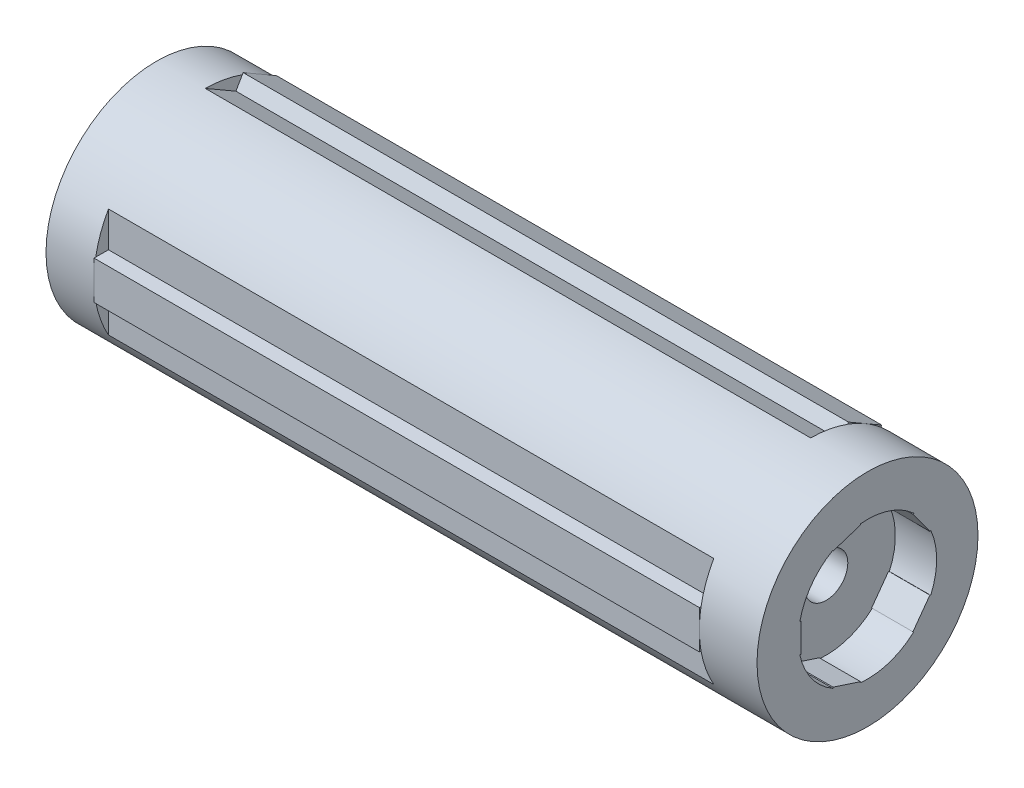
SolidWorks part; units mm, degrees
material "PVC hart"
ref_plane "Ebene vorne" through (0, 0, 0) normal (0, 0, 1) x (1, 0, 0)
ref_plane "Ebene oben" through (0, 0, 0) normal (0, 1, 0) x (1, 0, 0)
ref_plane "Ebene rechts" through (0, 0, 0) normal (1, 0, 0) x (0, 0, -1)
sketch "Skizze1" plane through (0, 0, 0) normal (1, 0, 0) x (0, 0, -1)
  circle A0 centre (0, 0) radius 11.5
  dimension "D1" = 23
extrude "Grundkörper Walze" add sketch "Skizze1" along normal blind 74
sketch "Skizze2" plane through (74, 0, 0) normal (1, 0, 0) x (0, 0, -1)
  line L0 (-15.3822, 0) -> (15.9559, 0) construction
  line L1 (-7.0405, 1.5073) -> (-6.9405, 1.5073)
  line L2 (-6.9405, 1.5073) -> (-6.9405, -1.4927)
  line L3 (-6.9405, -1.4927) -> (-7.0436, -1.4927)
  line L4 (-0.7421, 7.1617) -> (-0.7112, 7.0666)
  line L5 (-0.7112, 7.0666) -> (-3.5643, 6.1395)
  line L6 (-3.5643, 6.1395) -> (-3.5962, 6.2376)
  line L7 (6.5818, 2.9188) -> (6.5009, 2.86)
  line L8 (6.5009, 2.86) -> (4.7376, 5.2871)
  line L9 (4.7376, 5.2871) -> (4.821, 5.3477)
  line L10 (4.8099, -5.3577) -> (4.729, -5.2989)
  line L11 (4.729, -5.2989) -> (6.4923, -2.8719)
  line L12 (6.4923, -2.8719) -> (6.5757, -2.9325)
  line L13 (-3.6092, -6.2301) -> (-3.5783, -6.135)
  line L14 (-3.5783, -6.135) -> (-0.7251, -7.062)
  line L15 (-0.7251, -7.062) -> (-0.757, -7.1601)
  arc A0 (-7.0436, -1.4927) -> (-3.6092, -6.2301) centre (0, 0) ccw
  arc A1 (-3.5962, 6.2376) -> (-7.0405, 1.5073) centre (0, 0) ccw
  arc A2 (4.821, 5.3477) -> (-0.7421, 7.1617) centre (0, 0) ccw
  arc A3 (6.5757, -2.9325) -> (6.5818, 2.9188) centre (0, 0) ccw
  arc A4 (-0.757, -7.1601) -> (4.8099, -5.3577) centre (0, 0) ccw
  point P28 (0, 0)
  dimension "D1" = 14.4
  dimension "D2" = 3
  dimension "D3" = 0.1
  dimension "D4" = 5
extrude "Presspassung Kugellager" cut sketch "Skizze2" against normal blind 4.3
sketch "Skizze3" plane through (69.7, 0, 0) normal (1, 0, 0) x (0, 0, -1)
  circle A0 centre (0, 0) radius 2.25
  dimension "D1" = 4.5
extrude "M4 Schraubenführung" cut sketch "Skizze3" against normal blind 4.5
sketch "Skizze4" plane through (0, 0, 0) normal (-1, 0, 0) x (0, 0, 1)
  circle A0 centre (0, 0) radius 9.6
  dimension "D1" = 19.2
extrude "Motoraussparung " cut sketch "Skizze4" against normal blind 12.75
sketch "Skizze7" plane through (74, 0, 0) normal (1, 0, 0) x (0, 0, -1)
  line L0 (0, 13.4409) -> (0, -14.2481) construction
  line L1 (-11.5, 7.5) -> (-10, 7.5)
  line L2 (-11.5, 7.5) -> (-11.5, -7.5)
  line L3 (-11.5, -7.5) -> (-10, -7.5)
  line L4 (-10, 7.5) -> (-10, -7.5)
  dimension "D1" = 1.5
  dimension "D2" = 15
  dimension "D3" = 10
extrude "Zerstörungselement Aussparung" cut sketch "Skizze7" against normal blind 63 from offset 6 offset against normal yes
sketch "Skizze8" plane through (0, 0, 10) normal (0, 0, 1) x (1, 0, 0)
  line L0 (68, -5.6789) -> (68, 5.6789) construction
  line L1 (5, 2) -> (68, 2)
  line L2 (5, 2) -> (5, -2)
  line L3 (5, -2) -> (68, -2)
  line L4 (68, 2) -> (68, -2)
  line L5 (5, 2) -> (68, -2) construction
  line L6 (5, -2) -> (68, 2) construction
  line L7 (55, 0) -> (-55, 0) construction
  point P0 (36.5, 0)
  dimension "D1" = 31.5
  dimension "D3" = 63
  dimension "D4" = 4
extrude "Zerstörungselement Rechteck" add sketch "Skizze8" along normal blind 1.5
sketch "Skizze10" plane through (12.75, 0, 0) normal (-1, 0, 0) x (0, 0, 1)
  line L1 (4.1398, -2.2968) -> (4.059, 2.4368)
  line L2 (4.059, 2.4368) -> (-0.0809, 4.7336)
  line L3 (-0.0809, 4.7336) -> (-4.1398, 2.2968)
  line L4 (-4.1398, 2.2968) -> (-4.059, -2.4368)
  line L5 (-4.059, -2.4368) -> (0.0809, -4.7336)
  line L6 (0.0809, -4.7336) -> (4.1398, -2.2968)
  circle A0 centre (0, 0) radius 4.1 construction
  dimension "D1" = 8.2
extrude "M5 Motor Mutter " cut sketch "Skizze10" against normal blind 12
sketch "Skizze12" plane through (24.75, 0, 0) normal (-1, 0, 0) x (0, 0, 1)
  circle A0 centre (0, 0) radius 3.1
  dimension "D1" = 6.2
extrude "M5 Auslauf Schraube" cut sketch "Skizze12" against normal blind 2
pattern_circular "Zerstörungselement Vervielfältigung" count 3 over 360 about axis through (0, 0, 0) along (1, 0, 0) of "Zerstörungselement Rechteck", "Zerstörungselement Aussparung"
sketch "Skizze13" plane through (65.2, 0, 0) normal (1, 0, 0) x (0, 0, -1)
  circle A0 centre (0, 0) radius 8.5
extrude "Innenausparung hohl" cut sketch "Skizze13" against normal blind 38
